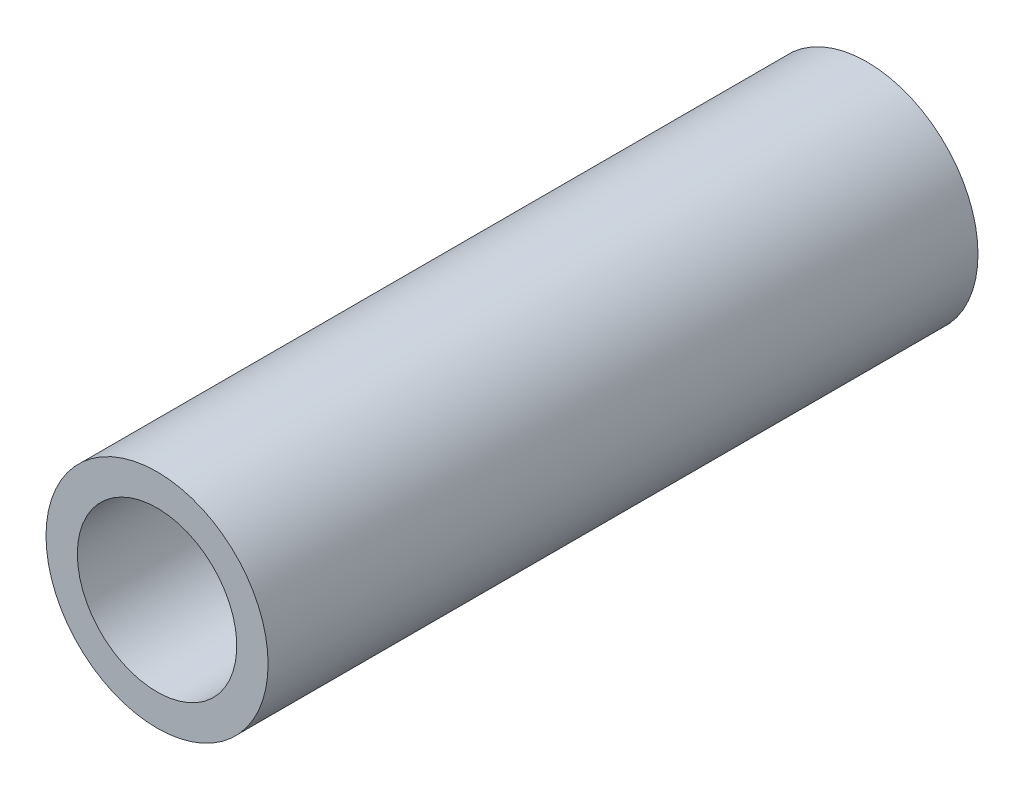
SolidWorks part; units mm, degrees
ref_plane "前视基准面" through (0, 0, 0) normal (0, 0, 1) x (1, 0, 0)
ref_plane "上视基准面" through (0, 0, 0) normal (0, 1, 0) x (1, 0, 0)
ref_plane "右视基准面" through (0, 0, 0) normal (1, 0, 0) x (0, 0, -1)
sketch "Sketch2" plane through (0, 0, 0) normal (0, 0, 1) x (1, 0, 0)
  circle A0 centre (0, 0) radius 14
  circle A1 centre (0, 0) radius 10.05
  dimension "D1" = 20.1
  dimension "D2" = 28
extrude "Extrude1" add sketch "Sketch2" along normal blind 89.5
